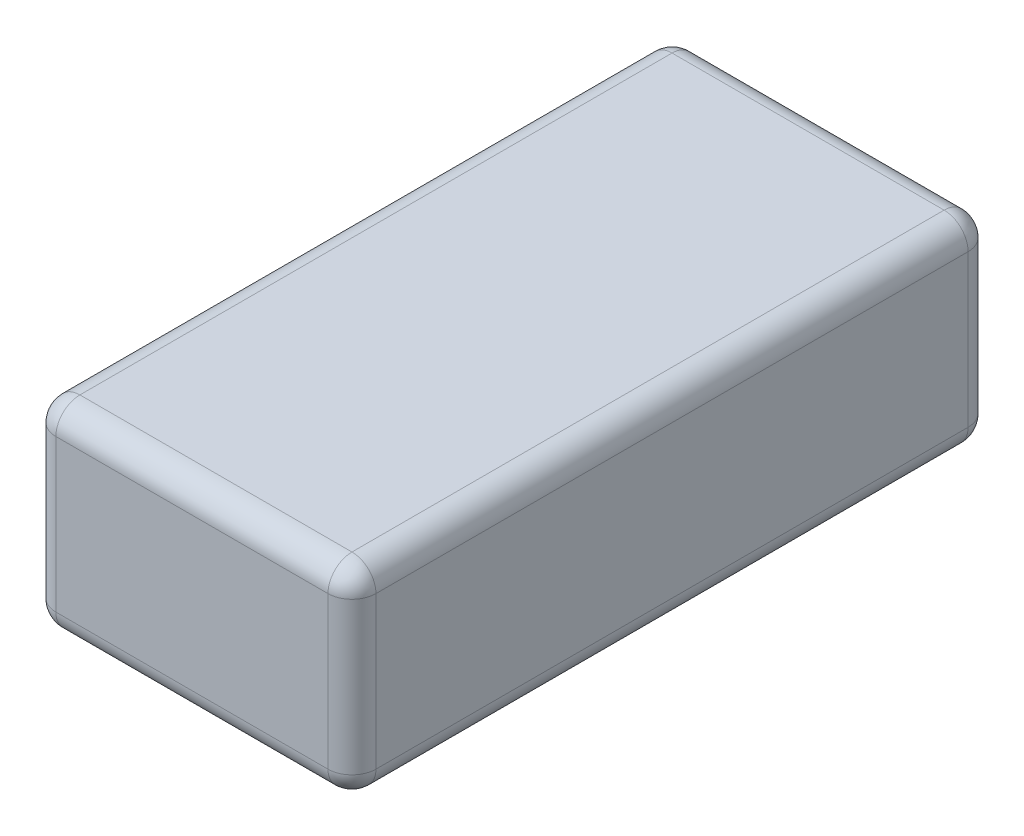
SolidWorks part; units mm, degrees
ref_plane "Front Plane" through (0, 0, 0) normal (0, 0, 1) x (1, 0, 0)
ref_plane "Top Plane" through (0, 0, 0) normal (0, 1, 0) x (1, 0, 0)
ref_plane "Right Plane" through (0, 0, 0) normal (1, 0, 0) x (0, 0, -1)
sketch "Sketch1" plane through (0, 0, 0) normal (0, 1, 0) x (1, 0, 0)
  line L1 (-20, 40) -> (20, 40)
  line L2 (-20, 40) -> (-20, -40)
  line L3 (-20, -40) -> (20, -40)
  line L4 (20, 40) -> (20, -40)
  line L5 (-20, 40) -> (20, -40) construction
  line L6 (-20, -40) -> (20, 40) construction
  point P0 (0, 0)
  dimension "D1" = 80
  dimension "D2" = 40
extrude "Boss-Extrude1" add sketch "Sketch1" along normal blind 25
fillet "Fillet2" radius 3 12 edges at (20, 12.5, -40) (-20, 12.5, -40) (-20, 12.5, 40) (20, 12.5, 40) (0, 25, 40) (-20, 25, 0) (0, 25, -40) (20, 25, 0) (0, 0, 40) (-20, 0, 0) (0, 0, -40) (20, 0, 0)
sketch "Sketch2" plane through (0, 0, 0) normal (0, -1, 0) x (1, 0, 0)
  line L0 (0, 37) -> (0, -37.692)
  line L1 (17, 37) -> (-17, 37) construction
